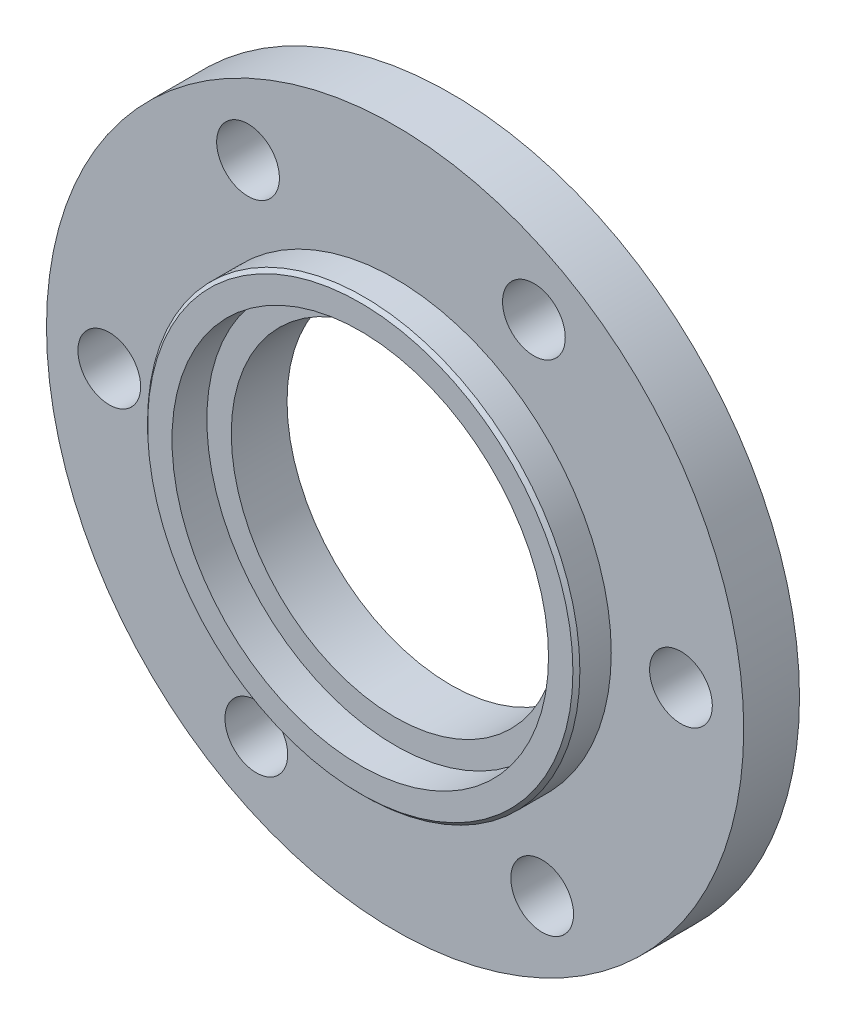
SolidWorks part; units mm, degrees
ref_plane "前视基准面" through (0, 0, 0) normal (0, 0, 1) x (1, 0, 0)
ref_plane "上视基准面" through (0, 0, 0) normal (0, 1, 0) x (1, 0, 0)
ref_plane "右视基准面" through (0, 0, 0) normal (1, 0, 0) x (0, 0, -1)
other "Configuration Table"
sketch "草图1" plane through (0, 0, 0) normal (0, 0, 1) x (1, 0, 0)
  circle A0 centre (0, 0) radius 50
  dimension "D1" = 100
extrude "凸台-拉伸1" add sketch "草图1" along normal blind 8
sketch "草图2" plane through (0, 0, 8) normal (0, 0, 1) x (1, 0, 0)
  circle A0 centre (0, 0) radius 31
  dimension "D1" = 62
extrude "凸台-拉伸2" add sketch "草图2" along normal blind 5
sketch "草图3" plane through (0, 0, 13) normal (0, 0, 1) x (1, 0, 0)
  circle A0 centre (0, 0) radius 27
  dimension "D1" = 54
extrude "切除-拉伸2" cut sketch "草图3" against normal blind 5
sketch "草图4" plane through (0, 0, 8) normal (0, 0, 1) x (1, 0, 0)
  circle A0 centre (0, 0) radius 23.5
  dimension "D1" = 47
extrude "切除-拉伸3" cut sketch "草图4" against normal through all
sketch "草图5" plane through (0, 0, 8) normal (0, 0, 1) x (1, 0, 0)
  line L0 (-65.2107, -0.0087) -> (78.3604, 0.9288) construction
  line L1 (0, 0) -> (0, 20.0892) construction
  circle A0 centre (40.9943, 0.6848) radius 4.5
  circle A1 centre (0, 0) radius 41 construction
  circle A2 centre (21.0902, -35.1597) radius 4.5
  circle A3 centre (-19.9041, -35.8445) radius 4.5
  circle A4 centre (-40.9943, -0.6848) radius 4.5
  circle A5 centre (-21.0902, 35.1597) radius 4.5
  circle A6 centre (19.9041, 35.8445) radius 4.5
  point P22 (0, 0)
  dimension "D1" = 9
  dimension "D2" = 82
  dimension "D3" = 6
extrude "切除-拉伸4" cut sketch "草图5" against normal through all
chamfer "倒角1" distance 0.5 angle 45 1 edges at (31, 0, 13)
